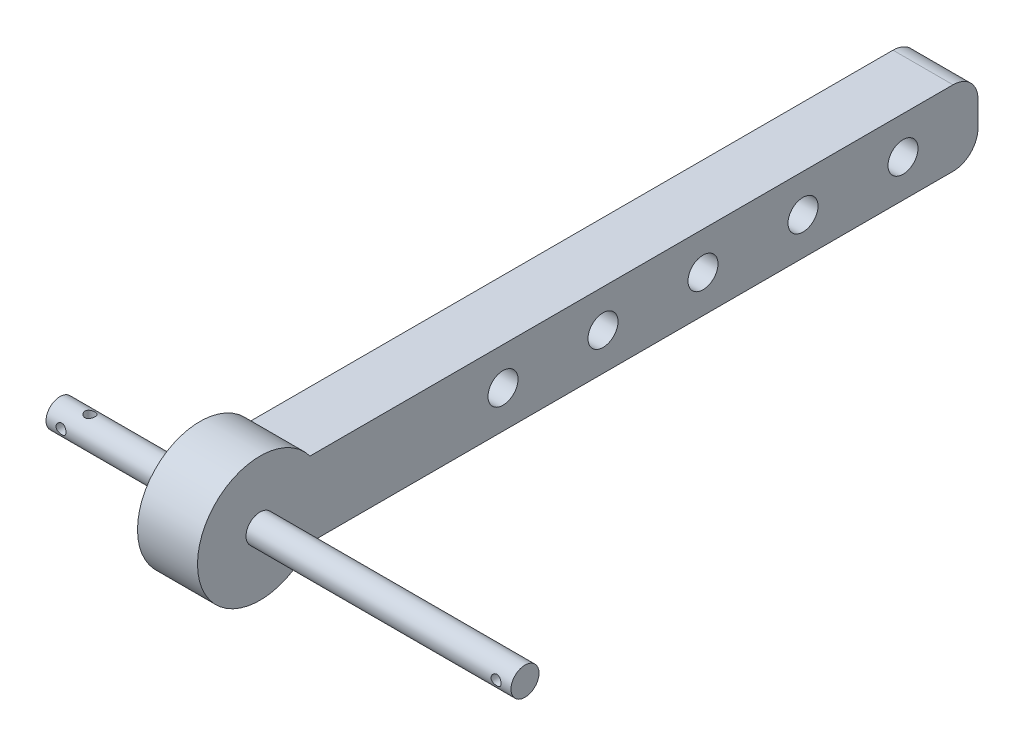
SolidWorks part; units mm, degrees
ref_plane "前视基准面" through (0, 0, 0) normal (0, 0, 1) x (1, 0, 0)
ref_plane "上视基准面" through (0, 0, 0) normal (0, 1, 0) x (1, 0, 0)
ref_plane "右视基准面" through (0, 0, 0) normal (1, 0, 0) x (0, 0, -1)
other "Configuration Table"
sketch "草图1" plane through (0, 0, 0) normal (1, 0, 0) x (0, 0, -1)
  line L1 (0, 0) -> (150, 0)
  line L2 (0, 0) -> (0, 15)
  line L3 (0, 15) -> (150, 15)
  line L4 (150, 0) -> (150, 15)
  dimension "D1" = 15
  dimension "D2" = 150
extrude "凸台-拉伸1" add sketch "草图1" along normal blind 12
fillet "圆角1" radius 5 4 edges at (6, 0, -150) (6, 15, -150) (6, 0, 0) (6, 15, 0)
sketch "草图6" plane through (12, 0, 0) normal (1, 0, 0) x (0, 0, -1)
  circle A0 centre (6.4, 7.5) radius 12.5
extrude "凸台-拉伸2" add sketch "草图6" against normal up to surface (12 mm away) up to face at (0, 7.5, -75)
sketch "草图15" plane through (0, 0, 0) normal (-1, 0, 0) x (0, 0, 1)
  circle A2 centre (-6.4, 7.5) radius 2.8
  dimension "D1" = 5.6
extrude "凸台-拉伸5" add sketch "草图15" along normal blind 28 and the other way blind 65
sketch "草图16" plane through (0, 0, 0) normal (0, 0, 1) x (1, 0, 0)
  line L0 (-28, 7.5) -> (-24.7951, 7.5) construction
  line L1 (-28, 10.3) -> (-28, 4.7) construction
  line L2 (65, 7.5) -> (28.4852, 7.5) construction
  line L3 (65, 4.7) -> (65, 10.3) construction
  circle A0 centre (-25, 7.5) radius 1
  circle A1 centre (62, 7.5) radius 1
  dimension "D2" = 2
  dimension "D3" = 2
  dimension "D1" = 3
  dimension "D4" = 3
extrude "切除-拉伸9" cut sketch "草图16" against normal up to next
sketch "草图17" plane through (0, 0, 0) normal (-1, 0, 0) x (0, 0, 1)
  line L0 (-150, 7.5) -> (-31.7081, 7.5) construction
  line L1 (-150, 5) -> (-150, 10) construction
  circle A0 centre (-135, 7.5) radius 3
  circle A1 centre (-115, 7.5) radius 3
  circle A2 centre (-95, 7.5) radius 3
  circle A3 centre (-75, 7.5) radius 3
  circle A4 centre (-55, 7.5) radius 3
  dimension "D6" = 6
  dimension "D7" = 6
  dimension "D8" = 6
  dimension "D9" = 6
  dimension "D10" = 6
  dimension "D1" = 15
  dimension "D2" = 20
  dimension "D3" = 20
  dimension "D4" = 20
  dimension "D5" = 20
extrude "切除-拉伸10" cut sketch "草图17" against normal up to next
sketch "草图18" plane through (0, 0, 0) normal (0, 1, 0) x (1, 0, 0)
  line L0 (-28, 6.4) -> (-12.4483, 6.4) construction
  line L1 (-28, 9.2) -> (-28, 3.6) construction
  circle A0 centre (-22, 6.4) radius 1
  dimension "D2" = 2
  dimension "D1" = 6
extrude "切除-拉伸11" cut sketch "草图18" along normal blind 15
